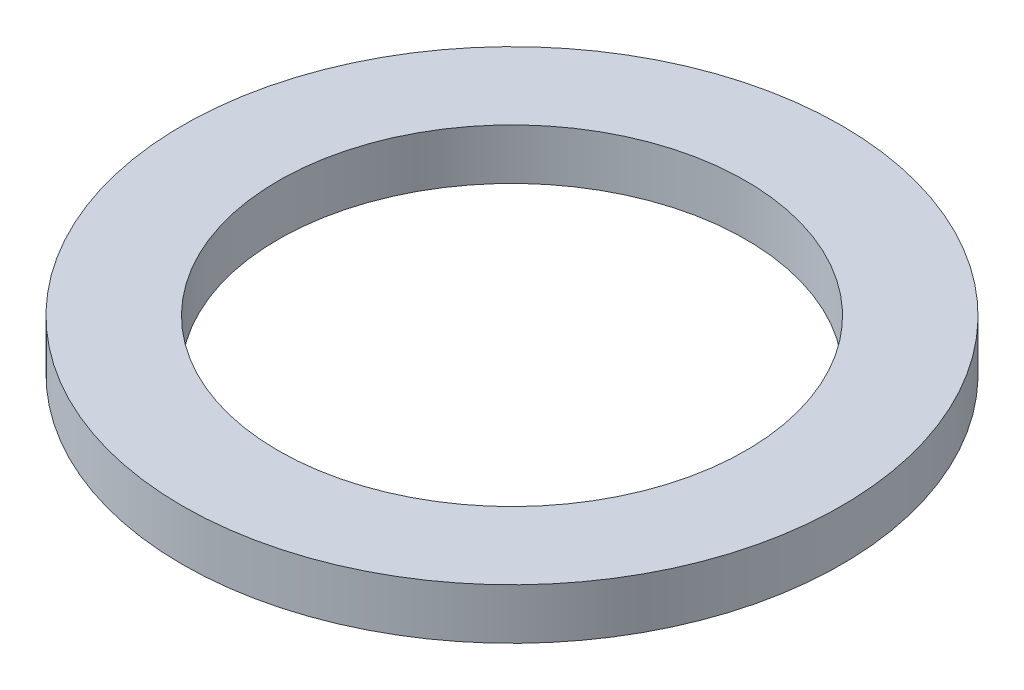
SolidWorks part; units mm, degrees
ref_plane "Front Plane" through (0, 0, 0) normal (0, 0, 1) x (1, 0, 0)
ref_plane "Top Plane" through (0, 0, 0) normal (0, 1, 0) x (1, 0, 0)
ref_plane "Right Plane" through (0, 0, 0) normal (1, 0, 0) x (0, 0, -1)
sketch "Sketch1" plane through (0, 0, 0) normal (0, 1, 0) x (1, 0, 0)
  circle A0 centre (0, 0) radius 20.6375
  circle A1 centre (0, 0) radius 14.6375
  dimension "D1" = 41.275
  dimension "D2" = 6
extrude "Boss-Extrude1" add sketch "Sketch1" along normal blind 3.175
